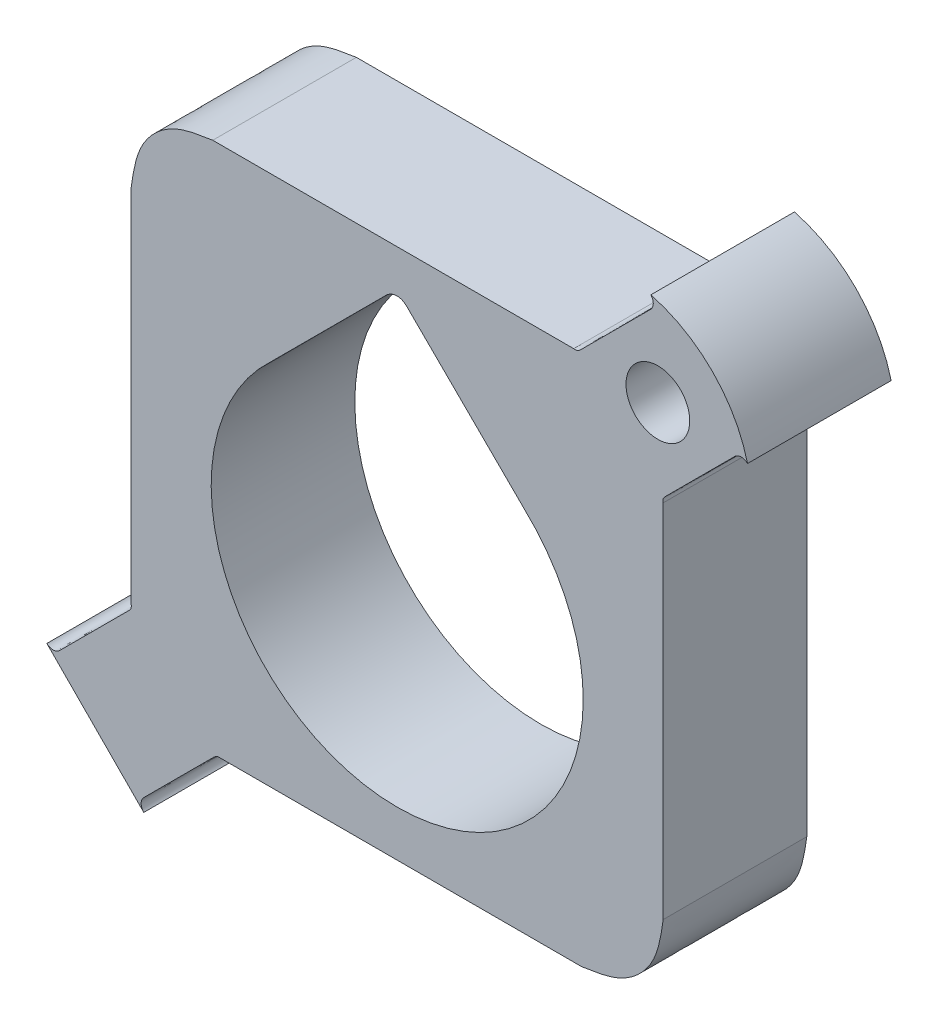
SolidWorks part; units mm, degrees
ref_plane "Front Plane" through (0, 0, 0) normal (0, 0, 1) x (1, 0, 0)
ref_plane "Top Plane" through (0, 0, 0) normal (0, 1, 0) x (1, 0, 0)
ref_plane "Right Plane" through (0, 0, 0) normal (1, 0, 0) x (0, 0, -1)
sketch "Sketch2" plane through (0, 0, 0) normal (0, 0, 1) x (1, 0, 0)
  line L0 (0, 45.4446) -> (0, 35.756) construction
  line L1 (0, 45.4446) -> (11.114, 45.4446) construction
  line L2 (0, 45.4446) -> (-11.114, 45.4446) construction
  line L3 (11.114, 45.4446) -> (14.8194, 45.4446) construction
  line L4 (-11.114, 45.4446) -> (-14.8194, 45.4446) construction
  line L5 (0, 35.756) -> (0, 32.0149) construction
  line L6 (0, 45.4446) -> (0, 57.9512) construction
  line L7 (-0.4438, 55.9843) -> (-5.2972, 51.1311)
  line L8 (5.2972, 51.1311) -> (0.4078, 55.9843)
  line L9 (-7.7062, 57.9512) -> (7.3729, 57.9512)
  line L10 (7.6431, 58.0344) -> (10.5964, 60.9874)
  line L11 (9.8185, 61.6923) -> (-7.7278, 61.6923) construction
  line L12 (-14.8194, 54.6007) -> (-14.8194, 37.0557) construction
  line L13 (-14.1152, 36.2786) -> (-11.198, 39.1954)
  line L14 (-11.114, 39.4645) -> (-11.114, 54.5429)
  line L15 (7.7061, 35.756) -> (-7.3717, 35.756)
  line L16 (-7.6423, 35.6721) -> (-10.5957, 32.7191)
  line L17 (-9.8171, 32.0149) -> (7.7257, 32.0149) construction
  line L18 (14.8194, 39.1086) -> (14.8194, 56.65) construction
  line L19 (14.1152, 57.4272) -> (11.1984, 54.5107)
  line L20 (11.114, 54.2423) -> (11.114, 39.1641)
  line L21 (0, 57.9512) -> (0, 61.6923) construction
  line L22 (14.1152, 57.4272) -> (10.5964, 60.9874) construction
  line L23 (-10.5957, 32.7191) -> (-14.1152, 36.2786) construction
  line L24 (14.6376, 57.4272) -> (10.5964, 61.509) construction
  line L25 (-14.6377, 36.2786) -> (-10.5875, 32.1898)
  line L26 (9.1644, 56.0499) -> (12.617, 59.4681) construction
  arc A0 (-5.2972, 51.1311) -> (5.2972, 51.1311) centre (0, 45.4446) ccw
  circle A2 centre (10.8907, 57.759) radius 1.3318
  arc A3 (-7.7278, 61.6923) -> (-14.8194, 54.6007) centre (-7.7278, 54.6007) ccw construction
  arc A4 (7.7257, 32.0149) -> (14.8194, 39.1086) centre (7.7257, 39.1086) ccw construction
  arc A6 (14.6376, 57.4272) -> (10.5964, 61.509) centre (9.1644, 56.0499) ccw
  spline S0 degree 3 poles (0.0001, 56.1691) (-0.0526, 56.164) (-0.161, 56.1535) (-0.3152, 56.0897) (-0.4012, 56.0192) (-0.4438, 55.9843) knots 0 0 0 0 0.322338 0.663828 1 1 1 1
  spline S2 degree 3 poles (0.4078, 55.9843) (0.3687, 56.0182) (0.2913, 56.0851) (0.1516, 56.1544) (0.0505, 56.1642) (0.0001, 56.1691) knots 0 0 0 0 0.338885 0.669777 1 1 1 1
  spline S3 degree 3 poles (7.3729, 57.9512) (7.3951, 57.9507) (7.4386, 57.9495) (7.5042, 57.9506) (7.5558, 57.9715) (7.5941, 57.9933) (7.6197, 58.0142) (7.6354, 58.0278) (7.6431, 58.0344) knots 0 0 0 0 0.227493 0.445972 0.663373 0.787115 0.896006 1 1 1 1
  spline S4 degree 3 poles (10.5964, 60.9874) (10.6255, 61.0267) (10.6835, 61.1053) (10.7077, 61.2534) (10.6806, 61.3894) (10.6309, 61.4704) (10.6007, 61.5044) (10.5964, 61.509) knots 0 0 0 0 0.104345 0.208931 0.313565 0.397995 0.411365 0.411365 0.411365 0.411365
  spline S6 degree 3 poles (-14.6377, 36.2786) (-14.6331, 36.2743) (-14.599, 36.2438) (-14.5182, 36.1934) (-14.3819, 36.1662) (-14.2334, 36.1905) (-14.1546, 36.2492) (-14.1152, 36.2786) knots 0.587566 0.587566 0.587566 0.587566 0.601007 0.685957 0.790142 0.895037 1 1 1 1
  spline S7 degree 3 poles (-11.198, 39.1954) (-11.1901, 39.2056) (-11.1745, 39.2255) (-11.1503, 39.2552) (-11.1254, 39.2935) (-11.1107, 39.3444) (-11.1073, 39.4043) (-11.1117, 39.4439) (-11.114, 39.4645) knots 0 0 0 0 0.131285 0.25763 0.390972 0.594165 0.788898 1 1 1 1
  spline S8 degree 3 poles (-11.114, 54.5429) (-11.0258, 55.1469) (-10.8533, 56.3272) (-9.4913, 57.6903) (-8.3106, 57.8629) (-7.7062, 57.9512) knots 0 0 0 0 0.33841 0.661392 1 1 1 1
  spline S9 degree 3 poles (-7.3717, 35.756) (-7.3908, 35.7572) (-7.4259, 35.7596) (-7.4804, 35.7568) (-7.5266, 35.7411) (-7.5688, 35.7217) (-7.6058, 35.6994) (-7.6298, 35.6815) (-7.6423, 35.6721) knots 0 0 0 0 0.196746 0.361608 0.557262 0.692766 0.839563 1 1 1 1
  spline S10 degree 3 poles (-10.5957, 32.7191) (-10.6247, 32.6798) (-10.6827, 32.6011) (-10.7067, 32.4529) (-10.6795, 32.3169) (-10.6277, 32.233) (-10.5944, 32.1967) (-10.5875, 32.1898) knots 0 0 0 0 0.104385 0.20895 0.313569 0.398093 0.419151 0.419151 0.419151 0.419151
  spline S12 degree 3 poles (14.6376, 57.4272) (14.6328, 57.4316) (14.5986, 57.4622) (14.5175, 57.5124) (14.3814, 57.5396) (14.233, 57.5152) (14.1545, 57.4565) (14.1152, 57.4272) knots 0.587538 0.587538 0.587538 0.587538 0.601601 0.686035 0.790672 0.895263 1 1 1 1
  spline S13 degree 3 poles (11.1984, 54.5107) (11.1897, 54.5006) (11.1727, 54.4807) (11.147, 54.4503) (11.1199, 54.4142) (11.108, 54.3634) (11.1091, 54.3046) (11.1123, 54.2639) (11.114, 54.2423) knots 0 0 0 0 0.134582 0.264928 0.404991 0.586048 0.77989 1 1 1 1
  spline S14 degree 3 poles (11.114, 39.1641) (11.0261, 38.56) (10.8542, 37.3794) (9.4914, 36.0167) (8.3105, 35.8443) (7.7061, 35.756) knots 0 0 0 0 0.338406 0.661372 1 1 1 1
  point P4 (13.0016, 34.3667)
  point P10 (-12.8822, 59.4713)
extrude "Boss-Extrude1" add sketch "Sketch2" along normal blind 6
